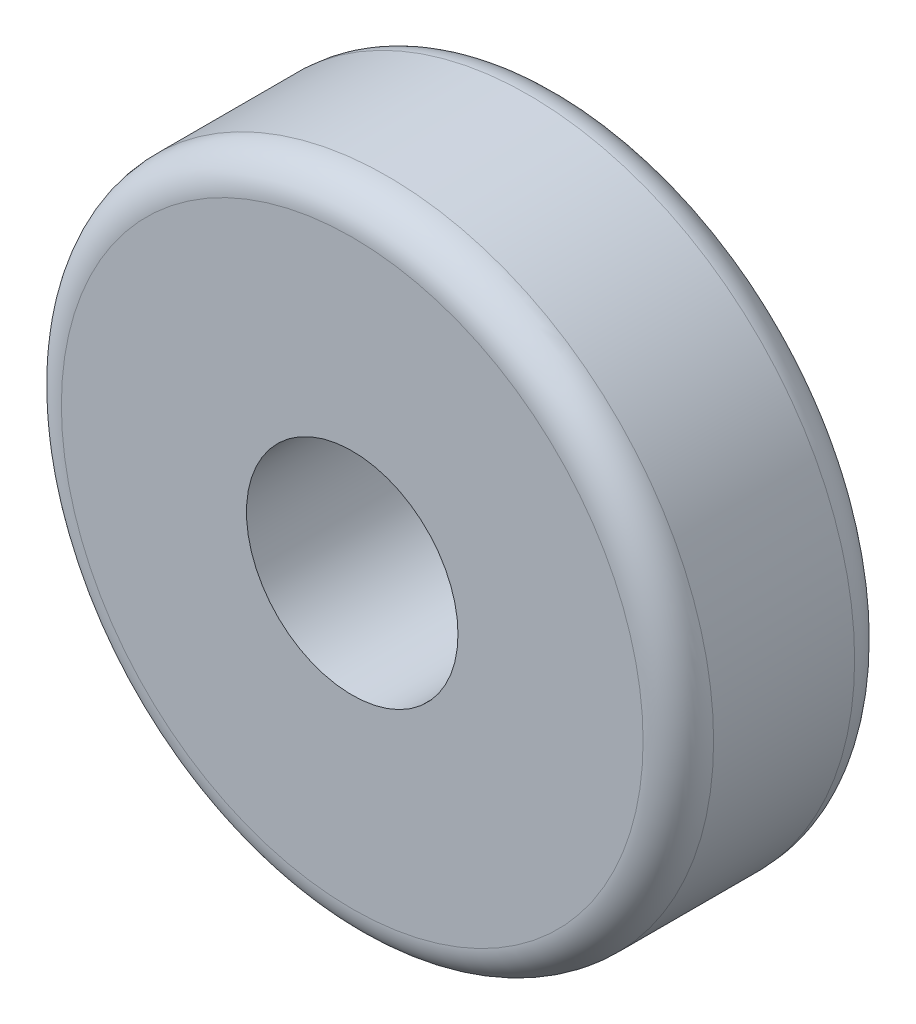
SolidWorks part; units mm, degrees
ref_plane "前视基准面" through (0, 0, 0) normal (0, 0, 1) x (1, 0, 0)
ref_plane "上视基准面" through (0, 0, 0) normal (0, 1, 0) x (1, 0, 0)
ref_plane "右视基准面" through (0, 0, 0) normal (1, 0, 0) x (0, 0, -1)
sketch "草图1" plane through (0, 0, 0) normal (0, 0, 1) x (1, 0, 0)
  circle A0 centre (0, 0) radius 18.5
  circle A1 centre (0, 0) radius 6
  dimension "D1" = 37
  dimension "D2" = 12
extrude "拉伸1" add sketch "草图1" along normal blind 12
fillet "圆角1" radius 2 1 edges at (18.5, 0, 12)
fillet "圆角2" radius 2 1 edges at (18.5, 0, 0)
